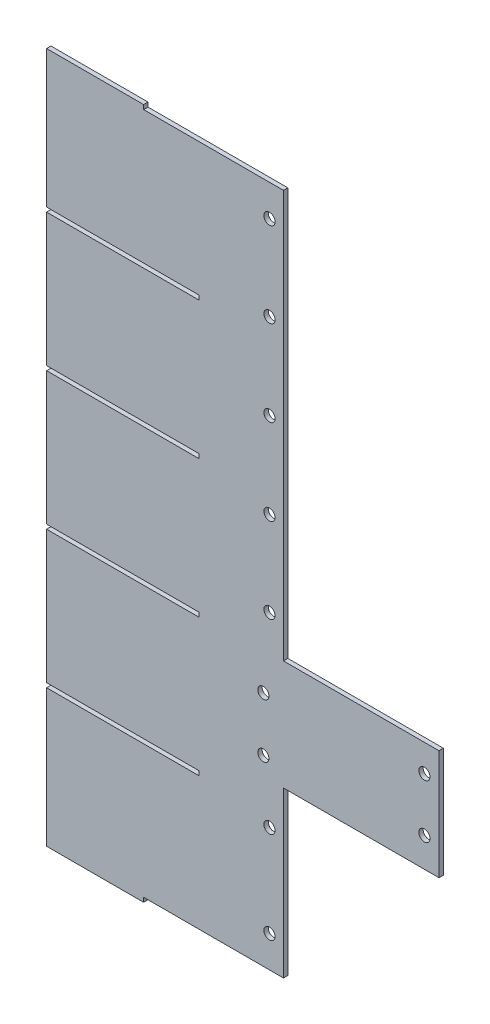
SolidWorks part; units mm, degrees
material "6061-T6 (SS)"
ref_plane "X-Y Datum" through (0, 0, 0) normal (0, 0, 1) x (1, 0, 0)
ref_plane "X-Z Datum" through (0, 0, 0) normal (0, 1, 0) x (1, 0, 0)
ref_plane "Y-Z Datum" through (0, 0, 0) normal (1, 0, 0) x (0, 0, -1)
sketch "Sketch1" plane through (0, 0, 0) normal (0, 0, 1) x (1, 0, 0)
  line L1 (129.0131, 254.2454) -> (-18.6854, 254.2454)
  line L3 (129.0131, -241.3467) -> (-18.6854, -241.3467)
  line L4 (-18.6854, 254.2454) -> (-18.6854, 157.667)
  line L24 (129.0131, 254.2454) -> (129.0131, -241.3467)
  line L25 (92.0885, 157.667) -> (-18.6854, 157.667)
  line L27 (92.0885, 154.492) -> (-18.6854, 154.492)
  line L29 (92.0885, 57.9136) -> (-18.6854, 57.9136)
  line L31 (92.0885, 54.7386) -> (-18.6854, 54.7386)
  line L33 (92.0885, -41.8399) -> (-18.6854, -41.8399)
  line L35 (92.0885, -45.0149) -> (-18.6854, -45.0149)
  line L37 (92.0885, -141.5933) -> (-18.6854, -141.5933)
  line L39 (92.0885, -144.7683) -> (-18.6854, -144.7683)
  line L41 (92.0885, -141.5933) -> (92.0885, -144.7683)
  line L42 (92.0885, -41.8399) -> (92.0885, -45.0149)
  line L43 (92.0885, 57.9136) -> (92.0885, 54.7386)
  line L44 (-18.6854, -144.7683) -> (-18.6854, -241.3467)
  line L45 (-18.6854, -45.0149) -> (-18.6854, -141.5933)
  line L46 (-18.6854, 54.7386) -> (-18.6854, -41.8399)
  line L47 (-18.6854, 154.492) -> (-18.6854, 57.9136)
  line L48 (92.0885, 157.667) -> (92.0885, 154.492)
extrude "Boss-Extrude2" add sketch "Sketch1" along normal blind 3.175
sketch "Sketch2" plane through (0, 0, 3.175) normal (0, 0, 1) x (1, 0, 0)
  line L0 (129.0131, -241.3467) -> (153.4072, -227.2627) construction
  line L2 (129.0131, 254.2454) -> (129.0131, -241.3467)
  line L15 (153.4072, -227.2627) -> (153.4072, -187.8927)
  line L18 (153.4072, -143.1808) -> (153.4072, 240.1614)
  line L19 (153.4072, 240.1614) -> (153.4072, 254.2454)
  line L21 (153.4072, -187.8927) -> (153.4072, -143.1808)
  line L22 (153.4072, 254.2454) -> (129.0131, 254.2454)
  line L23 (129.0131, -241.3467) -> (153.4072, -241.3467)
  line L24 (153.4072, -241.3467) -> (153.4072, -227.2627)
extrude "Boss-Extrude3" add sketch "Sketch2" against normal through all
sketch "Sketch3" plane through (0, 0, 3.175) normal (0, 0, 1) x (1, 0, 0)
  line L8 (153.4072, 6.4494) -> (-81.8872, 6.4494) construction
  line L9 (51.8072, 257.4204) -> (51.8072, 254.2454)
  line L18 (153.4072, 257.4204) -> (51.8072, 257.4204)
  line L19 (153.4072, 257.4204) -> (153.4072, 270.1204)
  line L20 (153.4072, 270.1204) -> (30.4963, 270.1204)
  line L21 (30.4963, 270.1204) -> (6.7146, 286.3764)
  line L22 (-18.6854, 286.3764) -> (6.7146, 286.3764)
  line L23 (-18.6854, 254.2454) -> (-18.6854, 286.3764)
  line L24 (51.8072, 254.2454) -> (-18.6854, 254.2454)
extrude "Boss-Extrude4" [suppressed] add sketch "Sketch3" against normal through all
sketch "Sketch4" [suppressed] plane through (0, 0, 3.175) normal (0, 0, 1) x (1, 0, 0)
  line L1 (153.4072, 270.1204) -> (221.7231, 270.1204)
  line L2 (153.4072, 270.1204) -> (153.4072, 257.4204)
  line L3 (153.4072, 257.4204) -> (221.7231, 257.4204)
  line L4 (221.7231, 270.1204) -> (221.7231, 257.4204)
  line L5 (153.4072, 254.2454) -> (221.7231, 254.2454)
  line L6 (153.4072, 254.2454) -> (153.4072, 157.667)
  line L7 (153.4072, 157.667) -> (221.7231, 157.667)
  line L8 (221.7231, 254.2454) -> (221.7231, 157.667)
  dimension "D1" = 68.3158
extrude "Boss-Extrude5" [suppressed] add sketch "Sketch4" against normal through all
sketch "Sketch7" plane through (0, 0, 3.175) normal (0, 0, 1) x (1, 0, 0)
  line L0 (92.0885, -41.8399) -> (153.4072, -41.8399) construction
  line L1 (153.2294, -121.7811) -> (153.4072, -41.8399)
  line L2 (153.4072, -241.3467) -> (153.4072, 254.2454) construction
  line L3 (153.4072, -41.8399) -> (266.4372, -41.8399)
  line L4 (266.4372, -41.8399) -> (266.4372, -121.7811)
  line L5 (266.4372, -121.7811) -> (153.2294, -121.7811)
  line L6 (153.4072, -241.3467) -> (153.4072, 254.2454) construction
extrude "Boss-Extrude6" add sketch "Sketch7" against normal through all
sketch "Sketch8" plane through (0, 0, 3.175) normal (0, 0, 1) x (1, 0, 0)
  line L1 (-18.6854, 254.2454) -> (51.8072, 254.2454)
  line L2 (-18.6854, 254.2454) -> (-18.6854, 257.4204)
  line L3 (-18.6854, 257.4204) -> (51.8072, 257.4204)
  line L4 (51.8072, 254.2454) -> (51.8072, 257.4204)
  line L5 (-18.6854, -241.3467) -> (51.8072, -241.3467)
  line L6 (-18.6854, -241.3467) -> (-18.6854, -244.5217)
  line L7 (-18.6854, -244.5217) -> (51.8072, -244.5217)
  line L8 (51.8072, -241.3467) -> (51.8072, -244.5217)
extrude "Boss-Extrude7" add sketch "Sketch8" against normal through all
sketch "Sketch12" plane through (0, 0, 3.175) normal (0, 0, 1) x (1, 0, 0)
  line L0 (-18.6854, 257.4204) -> (289.5814, 257.4204) construction
  line L1 (-18.6854, 257.4204) -> (-18.6854, -144.2662) construction
  line L2 (-18.6854, -144.2662) -> (289.5814, -144.2662) construction
  line L3 (289.5814, 257.4204) -> (289.5814, -144.2662) construction
  point P0 (143.2472, 244.0133)
  point P1 (143.2472, 171.1213)
  point P2 (143.2472, 98.2292)
  point P3 (143.2472, 25.3372)
  point P4 (143.2472, -47.5549)
  point P5 (170.6792, -74.9869)
  point P6 (210.7117, -74.9869)
  point P7 (250.7441, -74.9869)
  point P8 (256.2772, -80.52)
  point P9 (256.2772, -106.7475)
  point P10 (256.2772, -132.9751)
  point P15 (143.2472, -160.6738)
  point P16 (143.2472, -195.8942)
  point P17 (143.2472, -231.1146)
sketch "Sketch14" plane through (0, 0, 0) normal (0, 0, -1) x (-1, 0, 0)
  line L0 (18.6854, -244.5217) -> (-23.3644, -244.5217) construction
  line L1 (18.6854, -244.5217) -> (18.6854, -226.8054) construction
  line L2 (18.6854, -226.8054) -> (-23.3644, -226.8054) construction
  line L3 (-23.3644, -244.5217) -> (-23.3644, -226.8054) construction
  line L4 (-258.5632, -117.2684) -> (-255.7997, -117.2684) construction
  line L5 (-255.7997, -117.2684) -> (-255.7997, -100.4453) construction
  circle A0 centre (-143.2472, -218.4146) radius 4.064
  circle A1 centre (-143.2472, -151.7533) radius 4.064
  circle A2 centre (-255.7997, -100.4453) radius 4.064
  circle A3 centre (-255.7997, -61.597) radius 4.064
  circle A4 centre (-143.2472, -16.4399) radius 4.064
  circle A5 centre (-143.2472, 45.2329) radius 4.064
  circle A6 centre (-143.2472, 107.4367) radius 4.064
  circle A7 centre (-143.2472, 169.6405) radius 4.064
  circle A8 centre (-143.2472, 231.3133) radius 4.064
  point P0 (-143.2472, -218.4146)
  point P1 (-143.2472, -151.7533)
  point P2 (-255.7997, -100.4453)
  point P3 (-255.7997, -61.597)
  point P4 (-143.2472, -16.4399)
  point P5 (-143.2472, 45.2329)
  point P6 (-143.2472, 107.4367)
  point P7 (-143.2472, 169.6405)
  point P8 (-143.2472, 231.3133)
  point P13 (18.6854, -244.5217)
  point P34 (-255.7997, -61.597)
  point P36 (18.6854, -244.5217)
extrude "Cut-Extrude1" cut sketch "Sketch14" against normal through all
sketch "Sketch15" plane through (0, 0, 0) normal (0, 0, -1) x (-1, 0, 0)
  line L0 (-141.8421, -108.5523) -> (-135.7421, -108.5523) construction
  line L1 (-141.8421, -69.242) -> (-135.7421, -69.242) construction
  line L2 (-266.4372, -121.7811) -> (-206.1233, -121.7811) construction
  line L3 (-266.4372, -121.7811) -> (-266.4372, -88.3371) construction
  line L4 (-266.4372, -88.3371) -> (-206.1233, -88.3371) construction
  line L5 (-206.1233, -121.7811) -> (-206.1233, -88.3371) construction
  circle A0 centre (-138.7921, -108.5523) radius 4.064
  circle A1 centre (-138.7921, -69.242) radius 4.064
  point P12 (-266.4372, -121.7811)
extrude "Cut-Extrude2" cut sketch "Sketch15" against normal through all
